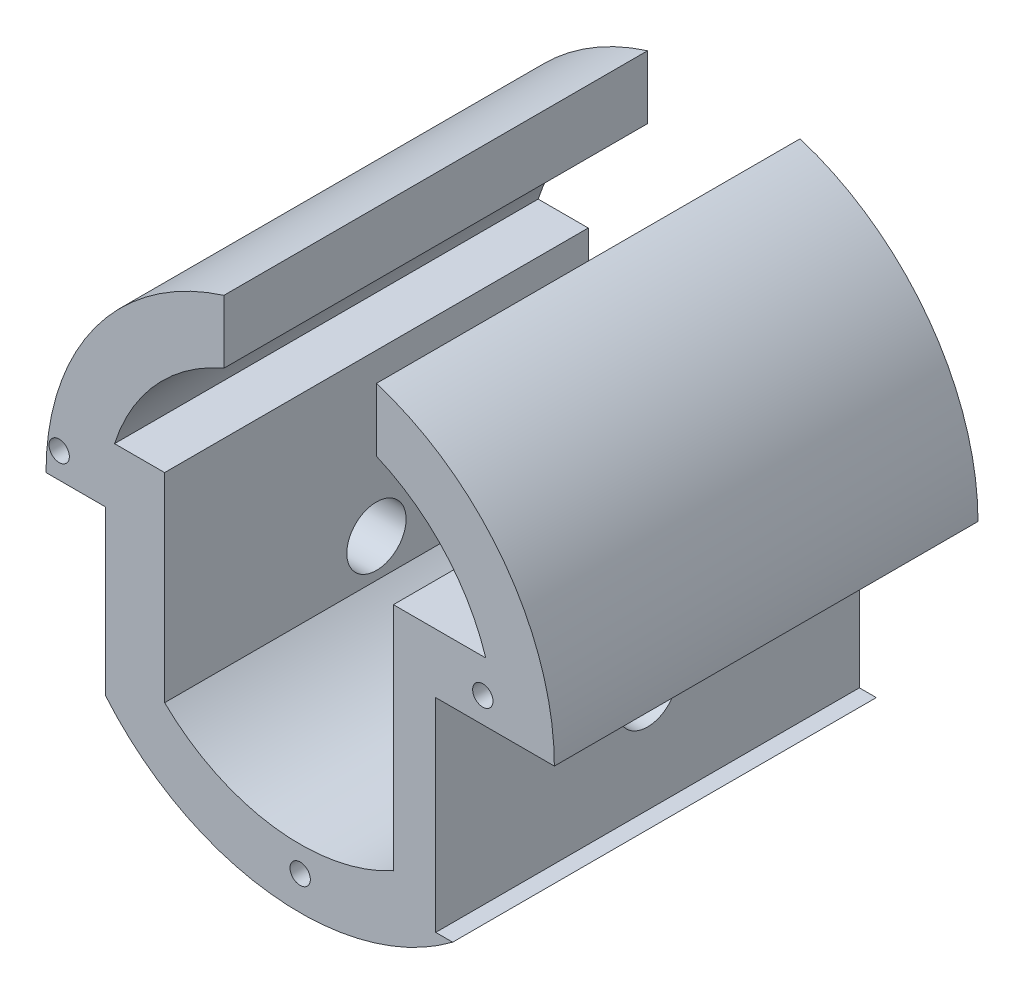
SolidWorks part; units mm, degrees
ref_plane "Piano frontale" through (0, 0, 0) normal (0, 0, 1) x (1, 0, 0)
ref_plane "Piano superiore" through (0, 0, 0) normal (0, 1, 0) x (1, 0, 0)
ref_plane "Piano destro" through (0, 0, 0) normal (1, 0, 0) x (0, 0, -1)
sketch "Schizzo1" plane through (0, 0, 0) normal (0, 0, 1) x (1, 0, 0)
  line L3 (-9, 28.6182) -> (9, 28.6182)
  line L4 (-30, 0) -> (-23, 0)
  line L5 (-23, 0) -> (-23, -19.2614)
  line L6 (30, 0) -> (18, 0)
  line L7 (18, 0) -> (18, -24)
  arc A1 (-9, 28.6182) -> (9, 28.6182) centre (0, 0) ccw
  dimension "D1" = 7
  dimension "D2" = 12
extrude "Estrusione-Estrusione1" add sketch "Schizzo1" along normal blind 50 contours L3 A1 L4 L5
shell "Svuota4" thickness 7
hole_wizard "Foro per Vite 5/16-1" positions "Schizzo4" profile "Schizzo5" hole size "5/16" standard "Ansi Inch"
sketch "Schizzo4" plane through (18, 0, 0) normal (1, 0, 0) x (0, 0, -1)
  line L1 (-50, -24) -> (0, -24) construction
  line L2 (-50, 0) -> (-50, -24) construction
  point P0 (-25, -12)
  dimension "D1" = 12
  dimension "D2" = 25
sketch "Schizzo5" plane through (18, -12, 25) normal (0, 1, 0) x (0, 0, -1)
  line L0 (0, 0) -> (0, 48)
  line L1 (0, 48) -> (3.5, 48)
  line L2 (3.5, 48) -> (3.5, 0)
  line L5 (3.5, 0) -> (0, 0)
  line L11 (0, -6.35) -> (0, 107.95) construction
  dimension "Thru Hole Dia." = 7
  dimension "Thru Hole Depth" = 48
sketch "Schizzo6" plane through (0, 28.6182, 0) normal (0, 1, 0) x (1, 0, 0)
  line L1 (9, -50) -> (-9, -50)
  line L2 (9, -50) -> (9, 0)
  line L3 (9, 0) -> (-9, 0)
  line L4 (-9, -50) -> (-9, 0)
extrude "Taglio-Estrusione1" cut sketch "Schizzo6" against normal blind 10
hole_wizard "Foro per Vite M2-1" positions "Schizzo11" profile "Schizzo12" hole size "M2" standard "ISO"
sketch "Schizzo11" plane through (0, 0, 50) normal (0, 0, 1) x (1, 0, 0)
  line L0 (-3.4444, 30.1387) -> (-3.4444, -29.8016) construction
  line L1 (-30, 0) -> (-23, 0) construction
  arc A0 (-23, -19.2614) -> (18, -24) centre (0, 0) ccw construction
  point P0 (0, -26)
  point P2 (-28.4444, 3)
  point P4 (21.5556, 3)
  dimension "D1" = 50
  dimension "D2" = 3
  dimension "D3" = 26
sketch "Schizzo12" plane through (0, -26, 50) normal (1, 0, 0) x (0, -1, 0)
  line L0 (0, 0) -> (0, 6.721)
  line L1 (0, 6.721) -> (1.2, 6)
  line L2 (1.2, 6) -> (1.2, 0)
  line L5 (1.2, 0) -> (0, 0)
  line L10 (0, 6.721) -> (-1.2, 6) construction
  line L11 (0, -6.35) -> (0, 107.95) construction
  dimension "Hole Dia." = 2.4
  dimension "Hole Depth" = 6
  dimension "Drill Angle" = 118
hole_wizard "Foro per Vite M2-2" positions "Schizzo13" profile "Schizzo14" hole size "M2" standard "ISO"
sketch "Schizzo13" plane through (0, 0, 0) normal (0, 0, -1) x (-1, 0, 0)
  line L0 (0, 27.794) -> (0, -33.7349) construction
  line L1 (-30, 0) -> (-18, 0) construction
  point P0 (0, -26)
  point P2 (-25, 3)
  point P4 (25, 3)
  dimension "D1" = 26
  dimension "D2" = 3
  dimension "D3" = 50
sketch "Schizzo14" plane through (0, -26, 0) normal (1, 0, 0) x (0, 1, 0)
  line L0 (0, 0) -> (0, 6.721)
  line L1 (0, 6.721) -> (1.2, 6)
  line L2 (1.2, 6) -> (1.2, 0)
  line L5 (1.2, 0) -> (0, 0)
  line L10 (0, 6.721) -> (-1.2, 6) construction
  line L11 (0, -6.35) -> (0, 107.95) construction
  dimension "Hole Dia." = 2.4
  dimension "Hole Depth" = 6
  dimension "Drill Angle" = 118
sketch "Schizzo17" plane through (18, 0, 0) normal (1, 0, 0) x (0, 0, -1)
  line L1 (-50, 0) -> (0, 0)
  line L2 (-50, 0) -> (-50, -24)
  line L3 (-50, -24) -> (0, -24)
  line L4 (0, 0) -> (0, -24)
sketch "Schizzo19" plane through (18, 0, 0) normal (1, 0, 0) x (0, 0, -1)
  line L1 (-50, 0) -> (0, 0)
  line L2 (-50, 0) -> (-50, -24)
  line L3 (-50, -24) -> (0, -24)
  line L4 (0, 0) -> (0, -24)
extrude "Taglio-Estrusione2" cut sketch "Schizzo19" against normal blind 2
